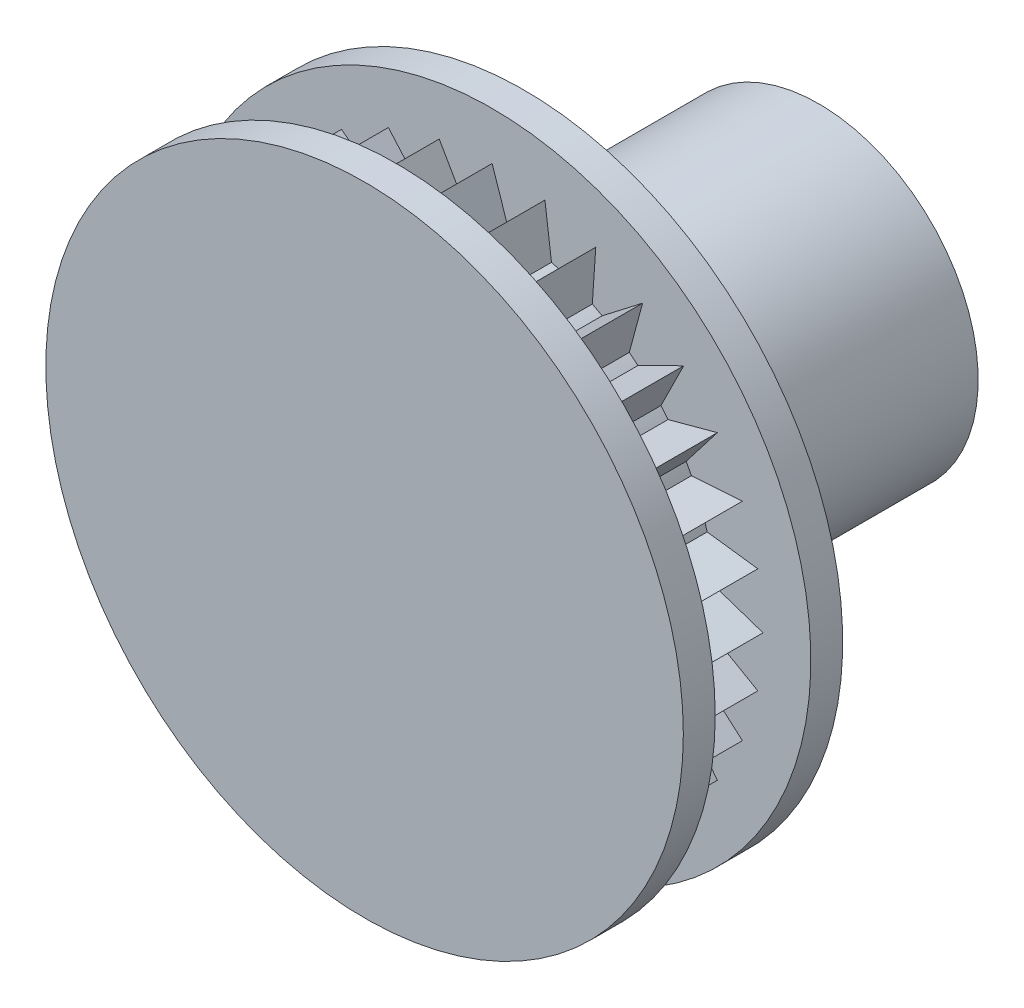
SolidWorks part; units mm, degrees
ref_plane "Front Plane" through (0, 0, 0) normal (0, 0, 1) x (1, 0, 0)
ref_plane "Top Plane" through (0, 0, 0) normal (0, 1, 0) x (1, 0, 0)
ref_plane "Right Plane" through (0, 0, 0) normal (1, 0, 0) x (0, 0, -1)
sketch "Sketch1" plane through (0, 0, 0) normal (0, 0, 1) x (1, 0, 0)
  line L0 (0, 33.4061) -> (0, 17) construction
  line L1 (0, 17) -> (1.0238, 13.9625)
  line L2 (0, 17) -> (-1.0238, 13.9625)
  line L3 (3.3165, 16.6733) -> (3.7281, 13.4945)
  line L4 (3.3165, 16.6733) -> (1.7198, 13.894)
  line L5 (6.5056, 15.706) -> (6.2891, 12.5079)
  line L6 (6.5056, 15.706) -> (4.3973, 13.2915)
  line L7 (9.4447, 14.135) -> (8.6084, 11.0406)
  line L8 (9.4447, 14.135) -> (6.9059, 12.1782)
  line L9 (12.0208, 12.0208) -> (10.5969, 9.149)
  line L10 (12.0208, 12.0208) -> (9.149, 10.5969)
  line L11 (14.135, 9.4447) -> (12.1782, 6.9059)
  line L12 (14.135, 9.4447) -> (11.0406, 8.6084)
  line L13 (15.706, 6.5056) -> (13.2915, 4.3973)
  line L14 (15.706, 6.5056) -> (12.5079, 6.2891)
  line L15 (16.6733, 3.3165) -> (13.894, 1.7198)
  line L16 (16.6733, 3.3165) -> (13.4945, 3.7281)
  line L17 (17, 0) -> (13.9625, -1.0238)
  line L18 (17, 0) -> (13.9625, 1.0238)
  line L19 (16.6733, -3.3165) -> (13.4945, -3.7281)
  line L20 (16.6733, -3.3165) -> (13.894, -1.7198)
  line L21 (15.706, -6.5056) -> (12.5079, -6.2891)
  line L22 (15.706, -6.5056) -> (13.2915, -4.3973)
  line L23 (14.135, -9.4447) -> (11.0406, -8.6084)
  line L24 (14.135, -9.4447) -> (12.1782, -6.9059)
  line L25 (12.0208, -12.0208) -> (9.149, -10.5969)
  line L26 (12.0208, -12.0208) -> (10.5969, -9.149)
  line L27 (9.4447, -14.135) -> (6.9059, -12.1782)
  line L28 (9.4447, -14.135) -> (8.6084, -11.0406)
  line L29 (6.5056, -15.706) -> (4.3973, -13.2915)
  line L30 (6.5056, -15.706) -> (6.2891, -12.5079)
  line L31 (3.3165, -16.6733) -> (1.7198, -13.894)
  line L32 (3.3165, -16.6733) -> (3.7281, -13.4945)
  line L33 (0, -17) -> (-1.0238, -13.9625)
  line L34 (0, -17) -> (1.0238, -13.9625)
  line L35 (-3.3165, -16.6733) -> (-3.7281, -13.4945)
  line L36 (-3.3165, -16.6733) -> (-1.7198, -13.894)
  line L37 (-6.5056, -15.706) -> (-6.2891, -12.5079)
  line L38 (-6.5056, -15.706) -> (-4.3973, -13.2915)
  line L39 (-9.4447, -14.135) -> (-8.6084, -11.0406)
  line L40 (-9.4447, -14.135) -> (-6.9059, -12.1782)
  line L41 (-12.0208, -12.0208) -> (-10.5969, -9.149)
  line L42 (-12.0208, -12.0208) -> (-9.149, -10.5969)
  line L43 (-14.135, -9.4447) -> (-12.1782, -6.9059)
  line L44 (-14.135, -9.4447) -> (-11.0406, -8.6084)
  line L45 (-15.706, -6.5056) -> (-13.2915, -4.3973)
  line L46 (-15.706, -6.5056) -> (-12.5079, -6.2891)
  line L47 (-16.6733, -3.3165) -> (-13.894, -1.7198)
  line L48 (-16.6733, -3.3165) -> (-13.4945, -3.7281)
  line L49 (-17, 0) -> (-13.9625, 1.0238)
  line L50 (-17, 0) -> (-13.9625, -1.0238)
  line L51 (-16.6733, 3.3165) -> (-13.4945, 3.7281)
  line L52 (-16.6733, 3.3165) -> (-13.894, 1.7198)
  line L53 (-15.706, 6.5056) -> (-12.5079, 6.2891)
  line L54 (-15.706, 6.5056) -> (-13.2915, 4.3973)
  line L55 (-14.135, 9.4447) -> (-11.0406, 8.6084)
  line L56 (-14.135, 9.4447) -> (-12.1782, 6.9059)
  line L57 (-12.0208, 12.0208) -> (-9.149, 10.5969)
  line L58 (-12.0208, 12.0208) -> (-10.5969, 9.149)
  line L59 (-9.4447, 14.135) -> (-6.9059, 12.1782)
  line L60 (-9.4447, 14.135) -> (-8.6084, 11.0406)
  line L61 (-6.5056, 15.706) -> (-4.3973, 13.2915)
  line L62 (-6.5056, 15.706) -> (-6.2891, 12.5079)
  line L63 (-3.3165, 16.6733) -> (-1.7198, 13.894)
  line L64 (-3.3165, 16.6733) -> (-3.7281, 13.4945)
  line L65 (0, -14) -> (0, -31.3573) construction
  line L66 (0, 14) -> (0, -10) construction
  circle A0 centre (0, 0) radius 20
  circle A1 centre (0, 0) radius 10
  arc A2 (-13.2915, 4.3973) -> (-13.4945, 3.7281) centre (0, 0) ccw
  circle A3 centre (0, 0) radius 17
  arc A4 (-13.4945, -3.7281) -> (-13.2915, -4.3973) centre (0, 0) ccw
  arc A5 (-12.5079, -6.2891) -> (-12.1782, -6.9059) centre (0, 0) ccw
  arc A6 (-11.0406, -8.6084) -> (-10.5969, -9.149) centre (0, 0) ccw
  arc A7 (-6.9059, -12.1782) -> (-6.2891, -12.5079) centre (0, 0) ccw
  arc A8 (-9.149, -10.5969) -> (-8.6084, -11.0406) centre (0, 0) ccw
  arc A9 (-4.3973, -13.2915) -> (-3.7281, -13.4945) centre (0, 0) ccw
  arc A10 (-1.7198, -13.894) -> (-1.0238, -13.9625) centre (0, 0) ccw
  arc A11 (1.0238, -13.9625) -> (1.7198, -13.894) centre (0, 0) ccw
  arc A12 (3.7281, -13.4945) -> (4.3973, -13.2915) centre (0, 0) ccw
  arc A13 (6.2891, -12.5079) -> (6.9059, -12.1782) centre (0, 0) ccw
  arc A14 (8.6084, -11.0406) -> (9.149, -10.5969) centre (0, 0) ccw
  arc A15 (10.5969, -9.149) -> (11.0406, -8.6084) centre (0, 0) ccw
  arc A16 (13.2915, -4.3973) -> (13.4945, -3.7281) centre (0, 0) ccw
  arc A17 (13.894, -1.7198) -> (13.9625, -1.0238) centre (0, 0) ccw
  arc A18 (13.9625, 1.0238) -> (13.894, 1.7198) centre (0, 0) ccw
  arc A19 (13.4945, 3.7281) -> (13.2915, 4.3973) centre (0, 0) ccw
  arc A20 (12.5079, 6.2891) -> (12.1782, 6.9059) centre (0, 0) ccw
  arc A21 (11.0406, 8.6084) -> (10.5969, 9.149) centre (0, 0) ccw
  arc A22 (9.149, 10.5969) -> (8.6084, 11.0406) centre (0, 0) ccw
  arc A23 (6.9059, 12.1782) -> (6.2891, 12.5079) centre (0, 0) ccw
  arc A24 (4.3973, 13.2915) -> (3.7281, 13.4945) centre (0, 0) ccw
  arc A25 (1.7198, 13.894) -> (1.0238, 13.9625) centre (0, 0) ccw
  arc A26 (-1.0238, 13.9625) -> (-1.7198, 13.894) centre (0, 0) ccw
  arc A27 (-3.7281, 13.4945) -> (-4.3973, 13.2915) centre (0, 0) ccw
  arc A28 (-6.2891, 12.5079) -> (-6.9059, 12.1782) centre (0, 0) ccw
  arc A29 (-8.6084, 11.0406) -> (-9.149, 10.5969) centre (0, 0) ccw
  arc A30 (-10.5969, 9.149) -> (-11.0406, 8.6084) centre (0, 0) ccw
  arc A31 (-12.1782, 6.9059) -> (-12.5079, 6.2891) centre (0, 0) ccw
  arc A32 (-13.894, 1.7198) -> (-13.9625, 1.0238) centre (0, 0) ccw
  arc A33 (-13.9625, -1.0238) -> (-13.894, -1.7198) centre (0, 0) ccw
  arc A34 (12.1782, -6.9059) -> (12.5079, -6.2891) centre (0, 0) ccw
  point P106 (0, 0)
  dimension "D1" = 40
  dimension "D2" = 20
  dimension "D3" = 28
  dimension "D4" = 34
  dimension "D5" = 32
extrude "Boss-Extrude1" add sketch "Sketch1" along normal blind 10 contours L24 A34 L21 L22 A16 L19 L20 A17 L17 L18 A18 L15 L16 A19 L13 L14 A20 L11 L12 A21 L9 L10 A22 L7 L8 A23 L5 L6 A24 L3 L4 A25 L1 L2 A26 L63 L64 A27 L61 L62 A28 L59 L60 A29 L57 L58 A30 L55 L56 A31 L53
sketch "Sketch2" plane through (0, 0, 10) normal (0, 0, 1) x (1, 0, 0)
  circle A0 centre (0, 0) radius 20
  dimension "D1" = 40
extrude "Boss-Extrude2" add sketch "Sketch2" against normal blind 2
sketch "Sketch3" plane through (0, 0, 0) normal (0, 0, -1) x (-1, 0, 0)
  circle A0 centre (0, 0) radius 20
  dimension "D1" = 40
extrude "Boss-Extrude3" add sketch "Sketch3" against normal blind 2
sketch "Sketch4" plane through (0, 0, 0) normal (0, 0, -1) x (-1, 0, 0)
  circle A0 centre (0, 0) radius 10
  circle A1 centre (0, 0) radius 0.05
  dimension "D1" = 20
  dimension "D2" = 0.1
extrude "Boss-Extrude4" add sketch "Sketch4" along normal blind 18.5
sketch "Sketch5" plane through (0, 0, 0) normal (0, 0, -1) x (-1, 0, 0)
  circle A0 centre (0, 0) radius 11
  dimension "D1" = 22
extrude "Boss-Extrude5" add sketch "Sketch5" along normal blind 3.5
